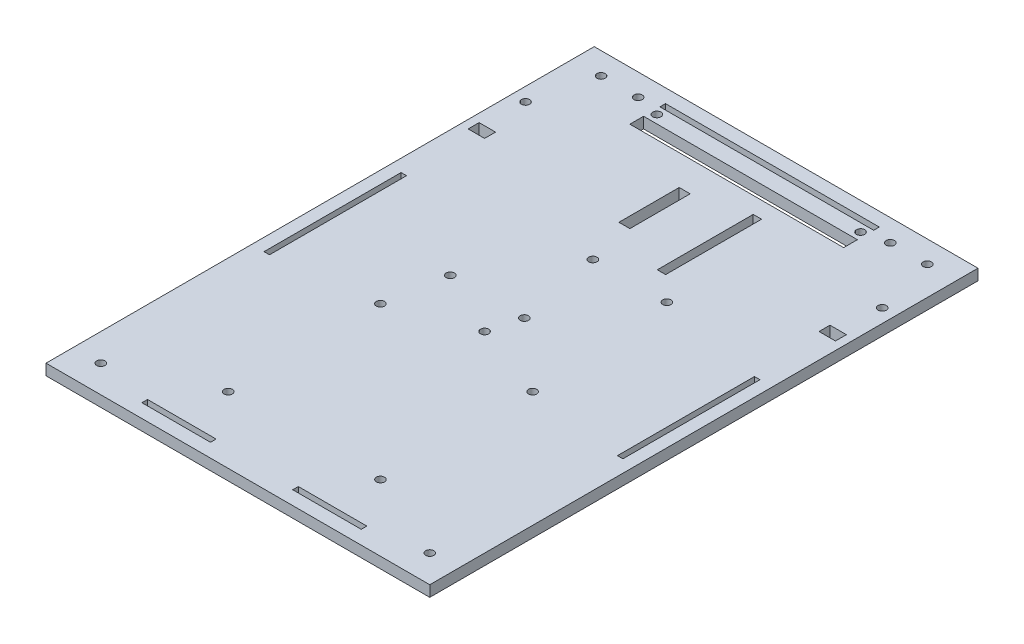
SolidWorks part; units mm, degrees
ref_plane "Front Plane" through (0, 0, 0) normal (0, 0, 1) x (1, 0, 0)
ref_plane "Top Plane" through (0, 0, 0) normal (0, 1, 0) x (1, 0, 0)
ref_plane "Right Plane" through (0, 0, 0) normal (1, 0, 0) x (0, 0, -1)
sketch "Sketch1" plane through (0, 0, 0) normal (0, 1, 0) x (1, 0, 0)
  line L1 (70, -100) -> (-70, -100)
  line L2 (70, -100) -> (70, 100)
  line L3 (70, 100) -> (-70, 100)
  line L4 (-70, -100) -> (-70, 100)
  line L5 (70, -100) -> (-70, 100) construction
  line L6 (70, 100) -> (-70, -100) construction
  point P0 (0, 0)
  dimension "D1" = 140
  dimension "D2" = 200
extrude "Boss-Extrude1" add sketch "Sketch1" along normal blind 4
sketch "Sketch2" plane through (0, 4, 0) normal (0, 1, 0) x (1, 0, 0)
  line L0 (0, 100) -> (0, -100) construction
  line L1 (70, 100) -> (-70, 100) construction
  line L2 (-70, -100) -> (70, -100) construction
  line L3 (0, 0) -> (-70, 0) construction
  line L4 (-70, 100) -> (-70, -100) construction
  line L6 (39, 80) -> (-39, 80)
  line L7 (39, 80) -> (39, 100)
  line L8 (39, 100) -> (-39, 100)
  line L9 (-39, 80) -> (-39, 100)
  line L10 (39, 80) -> (-39, 100) construction
  line L11 (39, 100) -> (-39, 80) construction
  line L12 (39, 92.95) -> (-39, 92.95)
  line L13 (39, 92.95) -> (39, 95)
  line L14 (39, 95) -> (-39, 95)
  line L15 (-39, 92.95) -> (-39, 95)
  line L16 (39, 92.95) -> (-39, 95) construction
  line L17 (39, 95) -> (-39, 92.95) construction
  line L18 (39, 82) -> (-39, 82)
  line L19 (39, 82) -> (39, 87)
  line L20 (39, 87) -> (-39, 87)
  line L21 (-39, 82) -> (-39, 87)
  line L22 (39, 82) -> (-39, 87) construction
  line L23 (39, 87) -> (-39, 82) construction
  circle A0 centre (-37.1508, 90) radius 1.5
  circle A1 centre (37.1508, 90) radius 1.5
  point P11 (0, 90)
  point P20 (0, 93.975)
  point P25 (0, 84.5)
  dimension "D3" = 3
  dimension "D4" = 1.8492
  dimension "D5" = 10
  dimension "D1" = 20
  dimension "D2" = 78
  dimension "D6" = 2.05
  dimension "D7" = 5
  dimension "D8" = 5
  dimension "D9" = 2
extrude "Cut-Extrude3" cut sketch "Sketch2" against normal through all contours L7 L14 L9 L12 | A0 | A1 | L7 L20 L9 L18
sketch "Sketch3" plane through (0, 4, 0) normal (0, 1, 0) x (1, 0, 0)
  line L0 (70, 100) -> (-70, 100) construction
  line L1 (-70.056, 95) -> (-60.056, 95)
  line L2 (-70.056, 95) -> (-70.056, 60)
  line L3 (-70.056, 60) -> (-60.056, 60)
  line L4 (-60.056, 95) -> (-60.056, 60)
  line L5 (-70.056, 95) -> (-60.056, 60) construction
  line L6 (-70.056, 60) -> (-60.056, 95) construction
  line L7 (-39, 82) -> (-39, 87) construction
  line L8 (0, 0) -> (0, 100) construction
  line L9 (-70, 100) -> (-70, -100) construction
  line L10 (-61, 51) -> (-67, 51)
  line L11 (-61, 51) -> (-61, 55)
  line L12 (-61, 55) -> (-67, 55)
  line L13 (-67, 51) -> (-67, 55)
  line L14 (-61, 51) -> (-67, 55) construction
  line L15 (-61, 55) -> (-67, 51) construction
  line L16 (61, 51) -> (61, 55)
  line L17 (61, 51) -> (67, 51)
  line L18 (67, 51) -> (67, 55)
  line L19 (61, 55) -> (67, 55)
  line L20 (70.056, 60) -> (60.056, 60)
  line L21 (70.056, 95) -> (70.056, 60)
  line L22 (70.056, 95) -> (60.056, 95)
  line L23 (60.056, 95) -> (60.056, 60)
  circle A0 centre (-65.056, 70) radius 1.5
  circle A1 centre (65.056, 70) radius 1.5
  point P0 (-65.056, 77.5)
  point P11 (-64, 53)
  dimension "D5" = 3
  dimension "D6" = 25
  dimension "D7" = 5
  dimension "D8" = 15
  dimension "D1" = 35
  dimension "D2" = 10
  dimension "D3" = 5
  dimension "D4" = 21.056
  dimension "D9" = 4
  dimension "D10" = 6
  dimension "D11" = 3
extrude "Cut-Extrude5" cut sketch "Sketch3" against normal through all contours L13 L10 L11 L12 | A1 | L19 L16 L17 L18 | A0
sketch "Sketch4" plane through (0, 4, 0) normal (0, 1, 0) x (1, 0, 0)
  line L0 (-70, 100) -> (-70, -100) construction
  line L1 (70, 100) -> (-70, 100) construction
  line L2 (0, 0) -> (0, 100) construction
  circle A0 centre (-46, 92) radius 1.5
  circle A1 centre (-59.5, 92) radius 1.5
  circle A2 centre (46, 92) radius 1.5
  circle A3 centre (59.5, 92) radius 1.5
  dimension "D1" = 3
  dimension "D2" = 3
  dimension "D4" = 10.5
  dimension "D5" = 8
  dimension "D6" = 8
  dimension "D3" = 13.5
extrude "Cut-Extrude6" cut sketch "Sketch4" against normal through all contours A3 | A1 | A0 | A2
sketch "Sketch6" plane through (0, 4, 0) normal (0, 1, 0) x (1, 0, 0)
  line L0 (0, 0) -> (0, 100) construction
  line L1 (70, 100) -> (-70, 100) construction
  line L3 (12, 76) -> (15.05, 76)
  line L4 (12, 76) -> (12, 41)
  line L5 (12, 41) -> (15.05, 41)
  line L6 (15.05, 76) -> (15.05, 41)
  line L7 (12, 76) -> (15.05, 41) construction
  line L8 (12, 41) -> (15.05, 76) construction
  line L9 (-10, 71) -> (-6, 71)
  line L10 (-10, 71) -> (-10, 49)
  line L11 (-10, 49) -> (-6, 49)
  line L12 (-6, 71) -> (-6, 49)
  line L13 (-10, 71) -> (-6, 49) construction
  line L14 (-10, 49) -> (-6, 71) construction
  line L15 (-70, -100) -> (70, -100) construction
  point P5 (13.525, 58.5)
  point P10 (-8, 60)
  dimension "D1" = 24
  dimension "D2" = 3.05
  dimension "D3" = 35
  dimension "D4" = 12
  dimension "D5" = 10
  dimension "D6" = 4
  dimension "D7" = 22
  dimension "D8" = 5
extrude "Cut-Extrude13" cut sketch "Sketch6" against normal blind 4
sketch "Sketch7" plane through (0, 4, 0) normal (0, 1, 0) x (1, 0, 0)
  line L0 (-70, 100) -> (-70, -100) construction
  line L1 (70, -88) -> (-70, -88)
  line L2 (70, -88) -> (70, -58)
  line L3 (70, -58) -> (-70, -58)
  line L4 (-70, -88) -> (-70, -58)
  line L5 (70, -88) -> (-70, -58) construction
  line L6 (70, -58) -> (-70, -88) construction
  line L8 (-70, -100) -> (70, -100) construction
  line L10 (0, 0) -> (0, 100) construction
  line L11 (-55, -56) -> (-30, -56)
  line L12 (-55, -56) -> (-55, 49)
  line L13 (-55, 49) -> (-30, 49)
  line L14 (-30, -56) -> (-30, 49)
  line L15 (-55, -56) -> (-30, 49) construction
  line L16 (-55, 49) -> (-30, -56) construction
  line L17 (70, 100) -> (-70, 100) construction
  line L18 (55, -56) -> (30, -56)
  line L19 (30, -56) -> (30, 49)
  line L20 (55, 49) -> (30, 49)
  line L21 (55, -56) -> (55, 49)
  line L23 (26, -3) -> (1, -3)
  line L24 (30, -78) -> (-30, -78)
  line L25 (30, -78) -> (30, -18)
  line L26 (30, -18) -> (-30, -18)
  line L27 (-30, -78) -> (-30, -18)
  line L28 (30, -78) -> (-30, -18) construction
  line L29 (30, -18) -> (-30, -78) construction
  line L30 (-26, 37) -> (-1, 37)
  line L31 (-26, 37) -> (-26, -3)
  line L32 (-26, -3) -> (-1, -3)
  line L33 (-1, 37) -> (-1, -3)
  line L34 (-26, 37) -> (-1, -3) construction
  line L35 (-26, -3) -> (-1, 37) construction
  line L36 (1, 37) -> (1, -3)
  line L37 (26, 37) -> (26, -3)
  line L38 (26, 37) -> (1, 37)
  line L39 (0, -48) -> (0, -18) construction
  line L40 (0, -48) -> (30, -48) construction
  circle A0 centre (-27.7642, -20.2358) radius 1.5
  circle A1 centre (27.7642, -20.2358) radius 1.5
  circle A2 centre (27.7642, -75.7642) radius 1.5
  circle A3 centre (-27.7642, -75.7642) radius 1.5
  circle A4 centre (-3, 32.5) radius 1.5
  circle A5 centre (-24, 1.5) radius 1.5
  circle A6 centre (3, 1.5) radius 1.5
  circle A7 centre (24, 32.5) radius 1.5
  point P0 (0, -73)
  point P13 (-42.5, -3.5)
  point P27 (0, -48)
  point P32 (-13.5, 17)
  dimension "D15" = 3
  dimension "D17" = 3
  dimension "D19" = 2
  dimension "D20" = 3
  dimension "D18" = 4.5
  dimension "D21" = 4.5
  dimension "D22" = 2
  dimension "D23" = 3
  dimension "D26" = 3
  dimension "D27" = 4.5
  dimension "D28" = 2
  dimension "D1" = 30
  dimension "D2" = 12
  dimension "D3" = 140
  dimension "D4" = 25
  dimension "D5" = 105
  dimension "D6" = 2
  dimension "D7" = 15
  dimension "D8" = 60
  dimension "D9" = 40
  dimension "D10" = 60
  dimension "D11" = 40
  dimension "D12" = 25
  dimension "D13" = 4
  dimension "D14" = 15
  dimension "D16" = 2.2358
  dimension "D24" = 2
  dimension "D25" = 4.5
extrude "Cut-Extrude15" cut sketch "Sketch7" against normal through all contours A1 | A3 | A2 | A7 | A6 | A5 | A4 | A0
sketch "Sketch8" plane through (0, 4, 0) normal (0, 1, 0) x (1, 0, 0)
  line L0 (-70, 100) -> (-70, -100) construction
  line L1 (-65.4567, -25) -> (-63.4567, -25)
  line L2 (-65.4567, -25) -> (-65.4567, 25)
  line L3 (-65.4567, 25) -> (-63.4567, 25)
  line L4 (-63.4567, -25) -> (-63.4567, 25)
  line L5 (-65.4567, -25) -> (-63.4567, 25) construction
  line L6 (-65.4567, 25) -> (-63.4567, -25) construction
  line L7 (-70, -100) -> (70, -100) construction
  line L8 (0, 0) -> (0, 100) construction
  line L9 (70, 100) -> (-70, 100) construction
  line L10 (65.4567, -25) -> (63.4567, -25)
  line L11 (63.4567, -25) -> (63.4567, 25)
  line L12 (65.4567, -25) -> (65.4567, 25)
  line L13 (65.4567, 25) -> (63.4567, 25)
  line L14 (70, -100) -> (70, 100) construction
  line L15 (15, -95) -> (15, -92.95)
  line L16 (-40, -95) -> (-15, -95)
  line L17 (-40, -95) -> (-40, -92.95)
  line L18 (-40, -92.95) -> (-15, -92.95)
  line L19 (-15, -95) -> (-15, -92.95)
  line L20 (-40, -95) -> (-15, -92.95) construction
  line L21 (-40, -92.95) -> (-15, -95) construction
  line L22 (40, -95) -> (15, -95)
  line L23 (40, -95) -> (40, -92.95)
  line L24 (40, -92.95) -> (15, -92.95)
  circle A0 centre (0, -10) radius 1.5
  circle A1 centre (-60, -90) radius 1.5
  circle A2 centre (60, -90) radius 1.5
  point P0 (-64.4567, 0)
  point P26 (-27.5, -93.975)
  dimension "D5" = 3
  dimension "D8" = 3
  dimension "D9" = 10
  dimension "D10" = 10
  dimension "D1" = 2
  dimension "D2" = 50
  dimension "D3" = 4.5433
  dimension "D4" = 75
  dimension "D6" = 90
  dimension "D7" = 70
  dimension "D11" = 2.05
  dimension "D12" = 30
  dimension "D13" = 25
  dimension "D14" = 5
extrude "Cut-Extrude16" cut sketch "Sketch8" against normal blind 4
